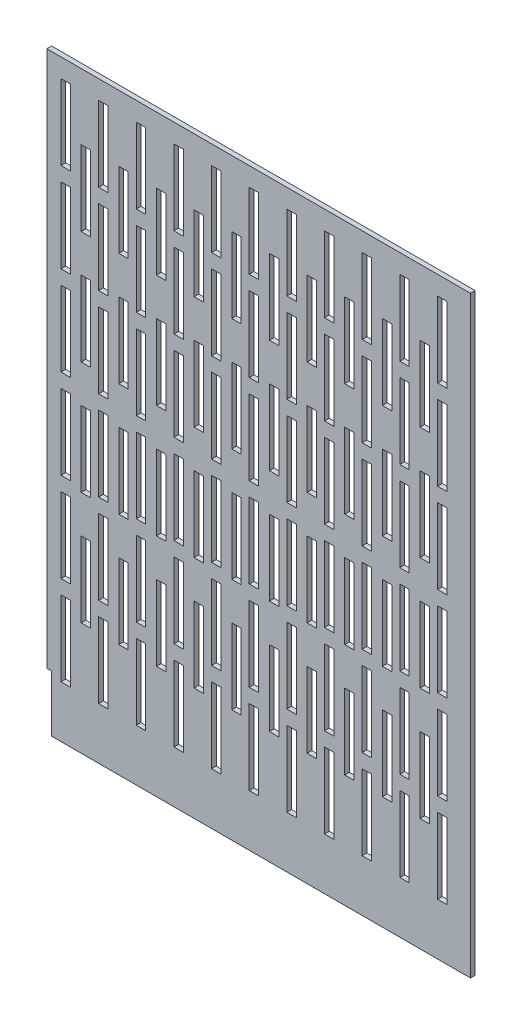
SolidWorks part; units mm, degrees
ref_plane "前视基准面" through (0, 0, 0) normal (0, 0, 1) x (1, 0, 0)
ref_plane "上视基准面" through (0, 0, 0) normal (0, 1, 0) x (1, 0, 0)
ref_plane "右视基准面" through (0, 0, 0) normal (1, 0, 0) x (0, 0, -1)
sketch "草图1" plane through (0, 0, 0) normal (0, 0, 1) x (1, 0, 0)
  line L0 (-45, 6) -> (-44.5, 6)
  line L1 (-45, 63) -> (0, 63)
  line L2 (-45, 63) -> (-45, 6)
  line L3 (-44.5, 0) -> (0, 0)
  line L4 (0, 63) -> (0, 0)
  line L5 (-44.5, 6) -> (-44.5, 0)
  point P2 (0, 0)
  dimension "D1" = 45
  dimension "D2" = 63
  dimension "D3" = 0.5
  dimension "D4" = 6
extrude "凸台-拉伸1" add sketch "草图1" along normal blind 0.5
sketch "草图3" plane through (0, 0, 0.5) normal (0, 0, 1) x (1, 0, 0)
  line L0 (-45, 63) -> (-45, 6) construction
  line L1 (-43.5, 61) -> (-42.5, 61)
  line L2 (-43.5, 61) -> (-43.5, 53)
  line L3 (-43.5, 53) -> (-42.5, 53)
  line L4 (-42.5, 61) -> (-42.5, 53)
  line L5 (0, 63) -> (-45, 63) construction
  line L6 (-39.5, 61) -> (-39.5, 53)
  line L7 (-39.5, 61) -> (-38.5, 61)
  line L8 (-38.5, 61) -> (-38.5, 53)
  line L9 (-39.5, 53) -> (-38.5, 53)
  line L10 (-35.5, 61) -> (-35.5, 53)
  line L11 (-35.5, 61) -> (-34.5, 61)
  line L12 (-34.5, 61) -> (-34.5, 53)
  line L13 (-35.5, 53) -> (-34.5, 53)
  line L14 (-31.5, 61) -> (-31.5, 53)
  line L15 (-31.5, 61) -> (-30.5, 61)
  line L16 (-30.5, 61) -> (-30.5, 53)
  line L17 (-31.5, 53) -> (-30.5, 53)
  line L18 (-27.5, 61) -> (-27.5, 53)
  line L19 (-27.5, 61) -> (-26.5, 61)
  line L20 (-26.5, 61) -> (-26.5, 53)
  line L21 (-27.5, 53) -> (-26.5, 53)
  line L22 (-23.5, 61) -> (-23.5, 53)
  line L23 (-23.5, 61) -> (-22.5, 61)
  line L24 (-22.5, 61) -> (-22.5, 53)
  line L25 (-23.5, 53) -> (-22.5, 53)
  line L26 (-19.5, 61) -> (-19.5, 53)
  line L27 (-19.5, 61) -> (-18.5, 61)
  line L28 (-18.5, 61) -> (-18.5, 53)
  line L29 (-19.5, 53) -> (-18.5, 53)
  line L30 (-15.5, 61) -> (-15.5, 53)
  line L31 (-15.5, 61) -> (-14.5, 61)
  line L32 (-14.5, 61) -> (-14.5, 53)
  line L33 (-15.5, 53) -> (-14.5, 53)
  line L34 (-11.5, 61) -> (-11.5, 53)
  line L35 (-11.5, 61) -> (-10.5, 61)
  line L36 (-10.5, 61) -> (-10.5, 53)
  line L37 (-11.5, 53) -> (-10.5, 53)
  line L38 (-7.5, 61) -> (-7.5, 53)
  line L39 (-7.5, 61) -> (-6.5, 61)
  line L40 (-6.5, 61) -> (-6.5, 53)
  line L41 (-7.5, 53) -> (-6.5, 53)
  line L42 (-3.5, 61) -> (-3.5, 53)
  line L43 (-3.5, 61) -> (-2.5, 61)
  line L44 (-2.5, 61) -> (-2.5, 53)
  line L45 (-3.5, 53) -> (-2.5, 53)
  line L46 (-43.5, 51.5) -> (-43.5, 43.5)
  line L47 (-43.5, 51.5) -> (-42.5, 51.5)
  line L48 (-42.5, 51.5) -> (-42.5, 43.5)
  line L49 (-43.5, 43.5) -> (-42.5, 43.5)
  line L50 (-39.5, 51.5) -> (-39.5, 43.5)
  line L51 (-39.5, 43.5) -> (-38.5, 43.5)
  line L52 (-38.5, 51.5) -> (-38.5, 43.5)
  line L53 (-39.5, 51.5) -> (-38.5, 51.5)
  line L54 (-35.5, 51.5) -> (-35.5, 43.5)
  line L55 (-35.5, 43.5) -> (-34.5, 43.5)
  line L56 (-34.5, 51.5) -> (-34.5, 43.5)
  line L57 (-35.5, 51.5) -> (-34.5, 51.5)
  line L58 (-31.5, 51.5) -> (-31.5, 43.5)
  line L59 (-31.5, 43.5) -> (-30.5, 43.5)
  line L60 (-30.5, 51.5) -> (-30.5, 43.5)
  line L61 (-31.5, 51.5) -> (-30.5, 51.5)
  line L62 (-27.5, 51.5) -> (-27.5, 43.5)
  line L63 (-27.5, 43.5) -> (-26.5, 43.5)
  line L64 (-26.5, 51.5) -> (-26.5, 43.5)
  line L65 (-27.5, 51.5) -> (-26.5, 51.5)
  line L66 (-23.5, 51.5) -> (-23.5, 43.5)
  line L67 (-23.5, 43.5) -> (-22.5, 43.5)
  line L68 (-22.5, 51.5) -> (-22.5, 43.5)
  line L69 (-23.5, 51.5) -> (-22.5, 51.5)
  line L70 (-19.5, 51.5) -> (-19.5, 43.5)
  line L71 (-19.5, 43.5) -> (-18.5, 43.5)
  line L72 (-18.5, 51.5) -> (-18.5, 43.5)
  line L73 (-19.5, 51.5) -> (-18.5, 51.5)
  line L74 (-15.5, 51.5) -> (-15.5, 43.5)
  line L75 (-15.5, 43.5) -> (-14.5, 43.5)
  line L76 (-14.5, 51.5) -> (-14.5, 43.5)
  line L77 (-15.5, 51.5) -> (-14.5, 51.5)
  line L78 (-11.5, 51.5) -> (-11.5, 43.5)
  line L79 (-11.5, 43.5) -> (-10.5, 43.5)
  line L80 (-10.5, 51.5) -> (-10.5, 43.5)
  line L81 (-11.5, 51.5) -> (-10.5, 51.5)
  line L82 (-7.5, 51.5) -> (-7.5, 43.5)
  line L83 (-7.5, 43.5) -> (-6.5, 43.5)
  line L84 (-6.5, 51.5) -> (-6.5, 43.5)
  line L85 (-7.5, 51.5) -> (-6.5, 51.5)
  line L86 (-3.5, 51.5) -> (-3.5, 43.5)
  line L87 (-3.5, 43.5) -> (-2.5, 43.5)
  line L88 (-2.5, 51.5) -> (-2.5, 43.5)
  line L89 (-3.5, 51.5) -> (-2.5, 51.5)
  line L90 (-43.5, 42) -> (-43.5, 34)
  line L91 (-43.5, 42) -> (-42.5, 42)
  line L92 (-42.5, 42) -> (-42.5, 34)
  line L93 (-43.5, 34) -> (-42.5, 34)
  line L94 (-39.5, 42) -> (-39.5, 34)
  line L95 (-39.5, 34) -> (-38.5, 34)
  line L96 (-38.5, 42) -> (-38.5, 34)
  line L97 (-39.5, 42) -> (-38.5, 42)
  line L98 (-35.5, 42) -> (-35.5, 34)
  line L99 (-35.5, 34) -> (-34.5, 34)
  line L100 (-34.5, 42) -> (-34.5, 34)
  line L101 (-35.5, 42) -> (-34.5, 42)
  line L102 (-31.5, 42) -> (-31.5, 34)
  line L103 (-31.5, 34) -> (-30.5, 34)
  line L104 (-30.5, 42) -> (-30.5, 34)
  line L105 (-31.5, 42) -> (-30.5, 42)
  line L106 (-27.5, 42) -> (-27.5, 34)
  line L107 (-27.5, 34) -> (-26.5, 34)
  line L108 (-26.5, 42) -> (-26.5, 34)
  line L109 (-27.5, 42) -> (-26.5, 42)
  line L110 (-23.5, 42) -> (-23.5, 34)
  line L111 (-23.5, 34) -> (-22.5, 34)
  line L112 (-22.5, 42) -> (-22.5, 34)
  line L113 (-23.5, 42) -> (-22.5, 42)
  line L114 (-19.5, 42) -> (-19.5, 34)
  line L115 (-19.5, 34) -> (-18.5, 34)
  line L116 (-18.5, 42) -> (-18.5, 34)
  line L117 (-19.5, 42) -> (-18.5, 42)
  line L118 (-15.5, 42) -> (-15.5, 34)
  line L119 (-15.5, 34) -> (-14.5, 34)
  line L120 (-14.5, 42) -> (-14.5, 34)
  line L121 (-15.5, 42) -> (-14.5, 42)
  line L122 (-11.5, 42) -> (-11.5, 34)
  line L123 (-11.5, 34) -> (-10.5, 34)
  line L124 (-10.5, 42) -> (-10.5, 34)
  line L125 (-11.5, 42) -> (-10.5, 42)
  line L126 (-7.5, 42) -> (-7.5, 34)
  line L127 (-7.5, 34) -> (-6.5, 34)
  line L128 (-6.5, 42) -> (-6.5, 34)
  line L129 (-7.5, 42) -> (-6.5, 42)
  line L130 (-3.5, 42) -> (-3.5, 34)
  line L131 (-3.5, 34) -> (-2.5, 34)
  line L132 (-2.5, 42) -> (-2.5, 34)
  line L133 (-3.5, 42) -> (-2.5, 42)
  line L134 (-43.5, 32.5) -> (-43.5, 24.5)
  line L135 (-43.5, 32.5) -> (-42.5, 32.5)
  line L136 (-42.5, 32.5) -> (-42.5, 24.5)
  line L137 (-43.5, 24.5) -> (-42.5, 24.5)
  line L138 (-39.5, 32.5) -> (-39.5, 24.5)
  line L139 (-39.5, 24.5) -> (-38.5, 24.5)
  line L140 (-38.5, 32.5) -> (-38.5, 24.5)
  line L141 (-39.5, 32.5) -> (-38.5, 32.5)
  line L142 (-35.5, 32.5) -> (-35.5, 24.5)
  line L143 (-35.5, 24.5) -> (-34.5, 24.5)
  line L144 (-34.5, 32.5) -> (-34.5, 24.5)
  line L145 (-35.5, 32.5) -> (-34.5, 32.5)
  line L146 (-31.5, 32.5) -> (-31.5, 24.5)
  line L147 (-31.5, 24.5) -> (-30.5, 24.5)
  line L148 (-30.5, 32.5) -> (-30.5, 24.5)
  line L149 (-31.5, 32.5) -> (-30.5, 32.5)
  line L150 (-27.5, 32.5) -> (-27.5, 24.5)
  line L151 (-27.5, 24.5) -> (-26.5, 24.5)
  line L152 (-26.5, 32.5) -> (-26.5, 24.5)
  line L153 (-27.5, 32.5) -> (-26.5, 32.5)
  line L154 (-23.5, 32.5) -> (-23.5, 24.5)
  line L155 (-23.5, 24.5) -> (-22.5, 24.5)
  line L156 (-22.5, 32.5) -> (-22.5, 24.5)
  line L157 (-23.5, 32.5) -> (-22.5, 32.5)
  line L158 (-19.5, 32.5) -> (-19.5, 24.5)
  line L159 (-19.5, 24.5) -> (-18.5, 24.5)
  line L160 (-18.5, 32.5) -> (-18.5, 24.5)
  line L161 (-19.5, 32.5) -> (-18.5, 32.5)
  line L162 (-15.5, 32.5) -> (-15.5, 24.5)
  line L163 (-15.5, 24.5) -> (-14.5, 24.5)
  line L164 (-14.5, 32.5) -> (-14.5, 24.5)
  line L165 (-15.5, 32.5) -> (-14.5, 32.5)
  line L166 (-11.5, 32.5) -> (-11.5, 24.5)
  line L167 (-11.5, 24.5) -> (-10.5, 24.5)
  line L168 (-10.5, 32.5) -> (-10.5, 24.5)
  line L169 (-11.5, 32.5) -> (-10.5, 32.5)
  line L170 (-7.5, 32.5) -> (-7.5, 24.5)
  line L171 (-7.5, 24.5) -> (-6.5, 24.5)
  line L172 (-6.5, 32.5) -> (-6.5, 24.5)
  line L173 (-7.5, 32.5) -> (-6.5, 32.5)
  line L174 (-3.5, 32.5) -> (-3.5, 24.5)
  line L175 (-3.5, 24.5) -> (-2.5, 24.5)
  line L176 (-2.5, 32.5) -> (-2.5, 24.5)
  line L177 (-3.5, 32.5) -> (-2.5, 32.5)
  line L178 (-43.5, 23) -> (-43.5, 15)
  line L179 (-43.5, 23) -> (-42.5, 23)
  line L180 (-42.5, 23) -> (-42.5, 15)
  line L181 (-43.5, 15) -> (-42.5, 15)
  line L182 (-39.5, 23) -> (-39.5, 15)
  line L183 (-39.5, 15) -> (-38.5, 15)
  line L184 (-38.5, 23) -> (-38.5, 15)
  line L185 (-39.5, 23) -> (-38.5, 23)
  line L186 (-35.5, 23) -> (-35.5, 15)
  line L187 (-35.5, 15) -> (-34.5, 15)
  line L188 (-34.5, 23) -> (-34.5, 15)
  line L189 (-35.5, 23) -> (-34.5, 23)
  line L190 (-31.5, 23) -> (-31.5, 15)
  line L191 (-31.5, 15) -> (-30.5, 15)
  line L192 (-30.5, 23) -> (-30.5, 15)
  line L193 (-31.5, 23) -> (-30.5, 23)
  line L194 (-27.5, 23) -> (-27.5, 15)
  line L195 (-27.5, 15) -> (-26.5, 15)
  line L196 (-26.5, 23) -> (-26.5, 15)
  line L197 (-27.5, 23) -> (-26.5, 23)
  line L198 (-23.5, 23) -> (-23.5, 15)
  line L199 (-23.5, 15) -> (-22.5, 15)
  line L200 (-22.5, 23) -> (-22.5, 15)
  line L201 (-23.5, 23) -> (-22.5, 23)
  line L202 (-19.5, 23) -> (-19.5, 15)
  line L203 (-19.5, 15) -> (-18.5, 15)
  line L204 (-18.5, 23) -> (-18.5, 15)
  line L205 (-19.5, 23) -> (-18.5, 23)
  line L206 (-15.5, 23) -> (-15.5, 15)
  line L207 (-15.5, 15) -> (-14.5, 15)
  line L208 (-14.5, 23) -> (-14.5, 15)
  line L209 (-15.5, 23) -> (-14.5, 23)
  line L210 (-11.5, 23) -> (-11.5, 15)
  line L211 (-11.5, 15) -> (-10.5, 15)
  line L212 (-10.5, 23) -> (-10.5, 15)
  line L213 (-11.5, 23) -> (-10.5, 23)
  line L214 (-7.5, 23) -> (-7.5, 15)
  line L215 (-7.5, 15) -> (-6.5, 15)
  line L216 (-6.5, 23) -> (-6.5, 15)
  line L217 (-7.5, 23) -> (-6.5, 23)
  line L218 (-3.5, 23) -> (-3.5, 15)
  line L219 (-3.5, 15) -> (-2.5, 15)
  line L220 (-2.5, 23) -> (-2.5, 15)
  line L221 (-3.5, 23) -> (-2.5, 23)
  line L222 (-43.5, 13.5) -> (-43.5, 5.5)
  line L223 (-43.5, 13.5) -> (-42.5, 13.5)
  line L224 (-42.5, 13.5) -> (-42.5, 5.5)
  line L225 (-43.5, 5.5) -> (-42.5, 5.5)
  line L226 (-39.5, 13.5) -> (-39.5, 5.5)
  line L227 (-39.5, 5.5) -> (-38.5, 5.5)
  line L228 (-38.5, 13.5) -> (-38.5, 5.5)
  line L229 (-39.5, 13.5) -> (-38.5, 13.5)
  line L230 (-35.5, 13.5) -> (-35.5, 5.5)
  line L231 (-35.5, 5.5) -> (-34.5, 5.5)
  line L232 (-34.5, 13.5) -> (-34.5, 5.5)
  line L233 (-35.5, 13.5) -> (-34.5, 13.5)
  line L234 (-31.5, 13.5) -> (-31.5, 5.5)
  line L235 (-31.5, 5.5) -> (-30.5, 5.5)
  line L236 (-30.5, 13.5) -> (-30.5, 5.5)
  line L237 (-31.5, 13.5) -> (-30.5, 13.5)
  line L238 (-27.5, 13.5) -> (-27.5, 5.5)
  line L239 (-27.5, 5.5) -> (-26.5, 5.5)
  line L240 (-26.5, 13.5) -> (-26.5, 5.5)
  line L241 (-27.5, 13.5) -> (-26.5, 13.5)
  line L242 (-23.5, 13.5) -> (-23.5, 5.5)
  line L243 (-23.5, 5.5) -> (-22.5, 5.5)
  line L244 (-22.5, 13.5) -> (-22.5, 5.5)
  line L245 (-23.5, 13.5) -> (-22.5, 13.5)
  line L246 (-19.5, 13.5) -> (-19.5, 5.5)
  line L247 (-19.5, 5.5) -> (-18.5, 5.5)
  line L248 (-18.5, 13.5) -> (-18.5, 5.5)
  line L249 (-19.5, 13.5) -> (-18.5, 13.5)
  line L250 (-15.5, 13.5) -> (-15.5, 5.5)
  line L251 (-15.5, 5.5) -> (-14.5, 5.5)
  line L252 (-14.5, 13.5) -> (-14.5, 5.5)
  line L253 (-15.5, 13.5) -> (-14.5, 13.5)
  line L254 (-11.5, 13.5) -> (-11.5, 5.5)
  line L255 (-11.5, 5.5) -> (-10.5, 5.5)
  line L256 (-10.5, 13.5) -> (-10.5, 5.5)
  line L257 (-11.5, 13.5) -> (-10.5, 13.5)
  line L258 (-7.5, 13.5) -> (-7.5, 5.5)
  line L259 (-7.5, 5.5) -> (-6.5, 5.5)
  line L260 (-6.5, 13.5) -> (-6.5, 5.5)
  line L261 (-7.5, 13.5) -> (-6.5, 13.5)
  line L262 (-3.5, 13.5) -> (-3.5, 5.5)
  line L263 (-3.5, 5.5) -> (-2.5, 5.5)
  line L264 (-2.5, 13.5) -> (-2.5, 5.5)
  line L265 (-3.5, 13.5) -> (-2.5, 13.5)
  line L266 (-37.3565, 56) -> (-37.3565, 48)
  line L267 (-41.3565, 56) -> (-40.3565, 56)
  line L268 (-41.3565, 56) -> (-41.3565, 48)
  line L269 (-41.3565, 48) -> (-40.3565, 48)
  line L270 (-40.3565, 56) -> (-40.3565, 48)
  line L271 (-37.3565, 56) -> (-36.3565, 56)
  line L272 (-36.3565, 56) -> (-36.3565, 48)
  line L273 (-37.3565, 48) -> (-36.3565, 48)
  line L274 (-33.3565, 56) -> (-33.3565, 48)
  line L275 (-33.3565, 56) -> (-32.3565, 56)
  line L276 (-32.3565, 56) -> (-32.3565, 48)
  line L277 (-33.3565, 48) -> (-32.3565, 48)
  line L278 (-29.3565, 56) -> (-29.3565, 48)
  line L279 (-29.3565, 56) -> (-28.3565, 56)
  line L280 (-28.3565, 56) -> (-28.3565, 48)
  line L281 (-29.3565, 48) -> (-28.3565, 48)
  line L282 (-25.3565, 56) -> (-25.3565, 48)
  line L283 (-25.3565, 56) -> (-24.3565, 56)
  line L284 (-24.3565, 56) -> (-24.3565, 48)
  line L285 (-25.3565, 48) -> (-24.3565, 48)
  line L286 (-21.3565, 56) -> (-21.3565, 48)
  line L287 (-21.3565, 56) -> (-20.3565, 56)
  line L288 (-20.3565, 56) -> (-20.3565, 48)
  line L289 (-21.3565, 48) -> (-20.3565, 48)
  line L290 (-17.3565, 56) -> (-17.3565, 48)
  line L291 (-17.3565, 56) -> (-16.3565, 56)
  line L292 (-16.3565, 56) -> (-16.3565, 48)
  line L293 (-17.3565, 48) -> (-16.3565, 48)
  line L294 (-13.3565, 56) -> (-13.3565, 48)
  line L295 (-13.3565, 56) -> (-12.3565, 56)
  line L296 (-12.3565, 56) -> (-12.3565, 48)
  line L297 (-13.3565, 48) -> (-12.3565, 48)
  line L298 (-9.3565, 56) -> (-9.3565, 48)
  line L299 (-9.3565, 56) -> (-8.3565, 56)
  line L300 (-8.3565, 56) -> (-8.3565, 48)
  line L301 (-9.3565, 48) -> (-8.3565, 48)
  line L302 (-5.3565, 56) -> (-5.3565, 48)
  line L303 (-5.3565, 56) -> (-4.3565, 56)
  line L304 (-4.3565, 56) -> (-4.3565, 48)
  line L305 (-5.3565, 48) -> (-4.3565, 48)
  line L306 (-41.3565, 44) -> (-41.3565, 36)
  line L307 (-41.3565, 44) -> (-40.3565, 44)
  line L308 (-40.3565, 44) -> (-40.3565, 36)
  line L309 (-41.3565, 36) -> (-40.3565, 36)
  line L310 (-37.3565, 44) -> (-37.3565, 36)
  line L311 (-37.3565, 36) -> (-36.3565, 36)
  line L312 (-36.3565, 44) -> (-36.3565, 36)
  line L313 (-37.3565, 44) -> (-36.3565, 44)
  line L314 (-33.3565, 44) -> (-33.3565, 36)
  line L315 (-33.3565, 36) -> (-32.3565, 36)
  line L316 (-32.3565, 44) -> (-32.3565, 36)
  line L317 (-33.3565, 44) -> (-32.3565, 44)
  line L318 (-29.3565, 44) -> (-29.3565, 36)
  line L319 (-29.3565, 36) -> (-28.3565, 36)
  line L320 (-28.3565, 44) -> (-28.3565, 36)
  line L321 (-29.3565, 44) -> (-28.3565, 44)
  line L322 (-25.3565, 44) -> (-25.3565, 36)
  line L323 (-25.3565, 36) -> (-24.3565, 36)
  line L324 (-24.3565, 44) -> (-24.3565, 36)
  line L325 (-25.3565, 44) -> (-24.3565, 44)
  line L326 (-21.3565, 44) -> (-21.3565, 36)
  line L327 (-21.3565, 36) -> (-20.3565, 36)
  line L328 (-20.3565, 44) -> (-20.3565, 36)
  line L329 (-21.3565, 44) -> (-20.3565, 44)
  line L330 (-17.3565, 44) -> (-17.3565, 36)
  line L331 (-17.3565, 36) -> (-16.3565, 36)
  line L332 (-16.3565, 44) -> (-16.3565, 36)
  line L333 (-17.3565, 44) -> (-16.3565, 44)
  line L334 (-13.3565, 44) -> (-13.3565, 36)
  line L335 (-13.3565, 36) -> (-12.3565, 36)
  line L336 (-12.3565, 44) -> (-12.3565, 36)
  line L337 (-13.3565, 44) -> (-12.3565, 44)
  line L338 (-9.3565, 44) -> (-9.3565, 36)
  line L339 (-9.3565, 36) -> (-8.3565, 36)
  line L340 (-8.3565, 44) -> (-8.3565, 36)
  line L341 (-9.3565, 44) -> (-8.3565, 44)
  line L342 (-5.3565, 44) -> (-5.3565, 36)
  line L343 (-5.3565, 36) -> (-4.3565, 36)
  line L344 (-4.3565, 44) -> (-4.3565, 36)
  line L345 (-5.3565, 44) -> (-4.3565, 44)
  line L346 (-41.3565, 32) -> (-41.3565, 24)
  line L347 (-41.3565, 32) -> (-40.3565, 32)
  line L348 (-40.3565, 32) -> (-40.3565, 24)
  line L349 (-41.3565, 24) -> (-40.3565, 24)
  line L350 (-37.3565, 32) -> (-37.3565, 24)
  line L351 (-37.3565, 24) -> (-36.3565, 24)
  line L352 (-36.3565, 32) -> (-36.3565, 24)
  line L353 (-37.3565, 32) -> (-36.3565, 32)
  line L354 (-33.3565, 32) -> (-33.3565, 24)
  line L355 (-33.3565, 24) -> (-32.3565, 24)
  line L356 (-32.3565, 32) -> (-32.3565, 24)
  line L357 (-33.3565, 32) -> (-32.3565, 32)
  line L358 (-29.3565, 32) -> (-29.3565, 24)
  line L359 (-29.3565, 24) -> (-28.3565, 24)
  line L360 (-28.3565, 32) -> (-28.3565, 24)
  line L361 (-29.3565, 32) -> (-28.3565, 32)
  line L362 (-25.3565, 32) -> (-25.3565, 24)
  line L363 (-25.3565, 24) -> (-24.3565, 24)
  line L364 (-24.3565, 32) -> (-24.3565, 24)
  line L365 (-25.3565, 32) -> (-24.3565, 32)
  line L366 (-21.3565, 32) -> (-21.3565, 24)
  line L367 (-21.3565, 24) -> (-20.3565, 24)
  line L368 (-20.3565, 32) -> (-20.3565, 24)
  line L369 (-21.3565, 32) -> (-20.3565, 32)
  line L370 (-17.3565, 32) -> (-17.3565, 24)
  line L371 (-17.3565, 24) -> (-16.3565, 24)
  line L372 (-16.3565, 32) -> (-16.3565, 24)
  line L373 (-17.3565, 32) -> (-16.3565, 32)
  line L374 (-13.3565, 32) -> (-13.3565, 24)
  line L375 (-13.3565, 24) -> (-12.3565, 24)
  line L376 (-12.3565, 32) -> (-12.3565, 24)
  line L377 (-13.3565, 32) -> (-12.3565, 32)
  line L378 (-9.3565, 32) -> (-9.3565, 24)
  line L379 (-9.3565, 24) -> (-8.3565, 24)
  line L380 (-8.3565, 32) -> (-8.3565, 24)
  line L381 (-9.3565, 32) -> (-8.3565, 32)
  line L382 (-5.3565, 32) -> (-5.3565, 24)
  line L383 (-5.3565, 24) -> (-4.3565, 24)
  line L384 (-4.3565, 32) -> (-4.3565, 24)
  line L385 (-5.3565, 32) -> (-4.3565, 32)
  line L386 (-41.3565, 20) -> (-41.3565, 12)
  line L387 (-41.3565, 20) -> (-40.3565, 20)
  line L388 (-40.3565, 20) -> (-40.3565, 12)
  line L389 (-41.3565, 12) -> (-40.3565, 12)
  line L390 (-37.3565, 20) -> (-37.3565, 12)
  line L391 (-37.3565, 12) -> (-36.3565, 12)
  line L392 (-36.3565, 20) -> (-36.3565, 12)
  line L393 (-37.3565, 20) -> (-36.3565, 20)
  line L394 (-33.3565, 20) -> (-33.3565, 12)
  line L395 (-33.3565, 12) -> (-32.3565, 12)
  line L396 (-32.3565, 20) -> (-32.3565, 12)
  line L397 (-33.3565, 20) -> (-32.3565, 20)
  line L398 (-29.3565, 20) -> (-29.3565, 12)
  line L399 (-29.3565, 12) -> (-28.3565, 12)
  line L400 (-28.3565, 20) -> (-28.3565, 12)
  line L401 (-29.3565, 20) -> (-28.3565, 20)
  line L402 (-25.3565, 20) -> (-25.3565, 12)
  line L403 (-25.3565, 12) -> (-24.3565, 12)
  line L404 (-24.3565, 20) -> (-24.3565, 12)
  line L405 (-25.3565, 20) -> (-24.3565, 20)
  line L406 (-21.3565, 20) -> (-21.3565, 12)
  line L407 (-21.3565, 12) -> (-20.3565, 12)
  line L408 (-20.3565, 20) -> (-20.3565, 12)
  line L409 (-21.3565, 20) -> (-20.3565, 20)
  line L410 (-17.3565, 20) -> (-17.3565, 12)
  line L411 (-17.3565, 12) -> (-16.3565, 12)
  line L412 (-16.3565, 20) -> (-16.3565, 12)
  line L413 (-17.3565, 20) -> (-16.3565, 20)
  line L414 (-13.3565, 20) -> (-13.3565, 12)
  line L415 (-13.3565, 12) -> (-12.3565, 12)
  line L416 (-12.3565, 20) -> (-12.3565, 12)
  line L417 (-13.3565, 20) -> (-12.3565, 20)
  line L418 (-9.3565, 20) -> (-9.3565, 12)
  line L419 (-9.3565, 12) -> (-8.3565, 12)
  line L420 (-8.3565, 20) -> (-8.3565, 12)
  line L421 (-9.3565, 20) -> (-8.3565, 20)
  line L422 (-5.3565, 20) -> (-5.3565, 12)
  line L423 (-5.3565, 12) -> (-4.3565, 12)
  line L424 (-4.3565, 20) -> (-4.3565, 12)
  line L425 (-5.3565, 20) -> (-4.3565, 20)
  dimension "D1" = 1
  dimension "D2" = 8
  dimension "D3" = 1.5
  dimension "D4" = 2
  dimension "D7" = 1
  dimension "D8" = 8
  dimension "D9" = 3
  dimension "D5" = 11
  dimension "D6" = 6
  dimension "D10" = 10
  dimension "D11" = 4
extrude "切除-拉伸1" cut sketch "草图3" against normal blind 0.5
